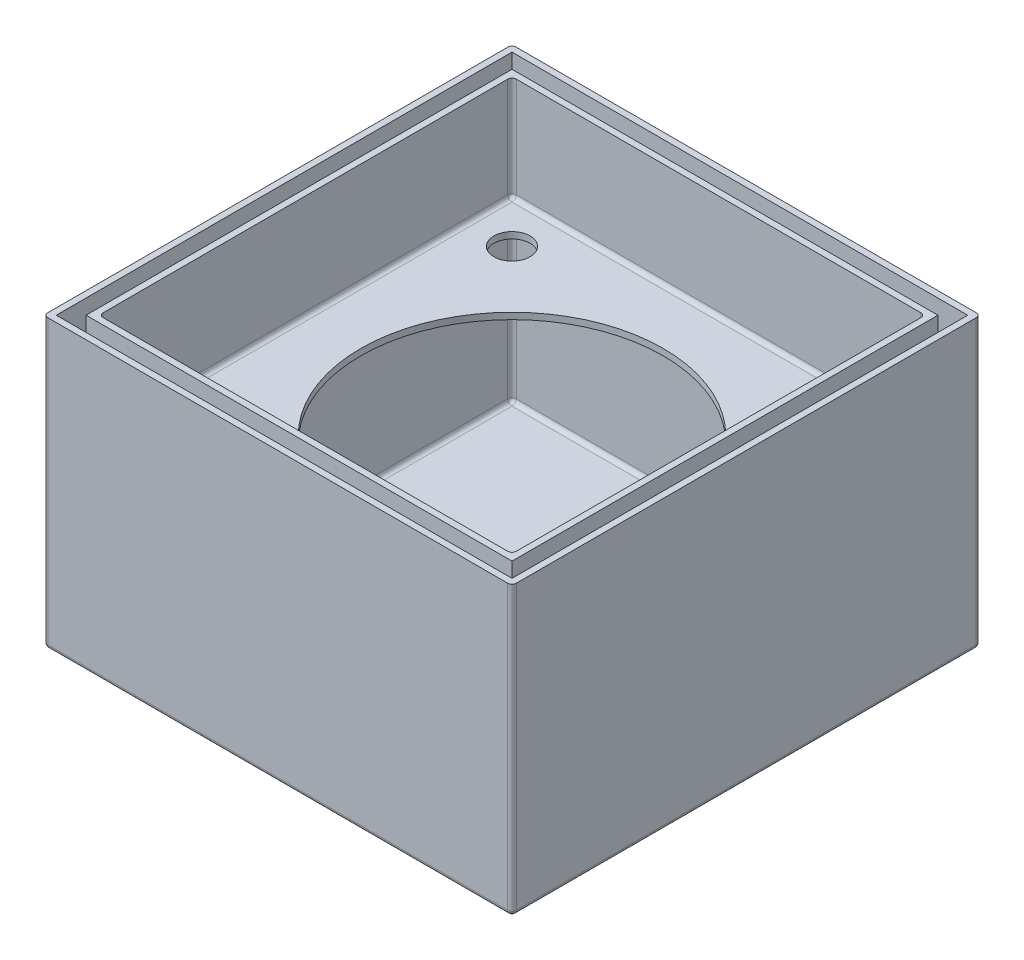
SolidWorks part; units mm, degrees
material "Nylon 101"
ref_plane "Front Plane" through (0, 0, 0) normal (0, 0, 1) x (1, 0, 0)
ref_plane "Top Plane" through (0, 0, 0) normal (0, 1, 0) x (1, 0, 0)
ref_plane "Right Plane" through (0, 0, 0) normal (1, 0, 0) x (0, 0, -1)
sketch "Sketch1" plane through (0, 0, 0) normal (0, 1, 0) x (1, 0, 0)
  line L0 (-100, 100) -> (100, 100)
  line L1 (-97, 97) -> (97, 97)
  line L2 (-97, 97) -> (-97, -97)
  line L3 (-97, -97) -> (97, -97)
  line L4 (97, 97) -> (97, -97)
  line L5 (-97, 97) -> (97, -97) construction
  line L6 (-97, -97) -> (97, 97) construction
  line L7 (100, 100) -> (100, -100)
  line L8 (-100, -100) -> (100, -100)
  line L9 (-100, 100) -> (-100, -100)
  line L10 (-107, -107) -> (107, -107)
  line L11 (107, 107) -> (107, -107)
  line L12 (-107, 107) -> (107, 107)
  line L13 (-107, 107) -> (-107, -107)
  line L14 (-110, -110) -> (110, -110)
  line L15 (110, 110) -> (110, -110)
  line L16 (-110, 110) -> (110, 110)
  line L17 (-110, 110) -> (-110, -110)
  point P0 (0, 0)
  dimension "D1" = 194
  dimension "D2" = 194
  dimension "D3" = 3
  dimension "D4" = 7
  dimension "D5" = 3
extrude "Boss-Extrude1" add sketch "Sketch1" along normal blind 132 contours L0 L9 L8 L7 L1 L4 L3 L2 | L16 L17 L14 L15 L13 L12 L11 L10
sketch "Sketch3" plane through (0, 0, 0) normal (0, -1, 0) x (1, 0, 0)
  line L1 (-110, -110) -> (110, -110)
  line L2 (-110, -110) -> (-110, 110)
  line L3 (-110, 110) -> (110, 110)
  line L4 (110, -110) -> (110, 110)
  line L5 (-110, -110) -> (110, 110) construction
  line L6 (-110, 110) -> (110, -110) construction
  point P0 (0, 0)
extrude "Boss-Extrude3" add sketch "Sketch3" along normal blind 3
ref_plane "Plane1" through (0, 80, 0) normal (0, 1, 0) x (1, 0, 0)
sketch "Sketch4" plane through (0, 80, 0) normal (0, 1, 0) x (1, 0, 0)
  line L1 (-97, -97) -> (97, -97)
  line L2 (-97, -97) -> (-97, 97)
  line L3 (-97, 97) -> (97, 97)
  line L4 (97, -97) -> (97, 97)
  line L5 (-97, -97) -> (97, 97) construction
  line L6 (-97, 97) -> (97, -97) construction
  point P0 (0, 0)
extrude "Boss-Extrude4" add sketch "Sketch4" along normal blind 3
sketch "Sketch5" plane through (0, 83, 0) normal (0, 1, 0) x (1, 0, 0)
  circle A0 centre (0, 0) radius 71
  dimension "D1" = 142
extrude "Cut-Extrude1" cut sketch "Sketch5" against normal blind 3
sketch "Sketch6" plane through (0, 83, 0) normal (0, 1, 0) x (1, 0, 0)
  line L0 (-97, 97) -> (97, 97) construction
  line L1 (97, -97) -> (97, 97) construction
  circle A0 centre (70, 70) radius 21.5154
  dimension "D1" = 27
  dimension "D2" = 27
extrude "Cut-Extrude2" [suppressed] cut sketch "Sketch6" against normal blind 3
sketch "Sketch7" plane through (0, 83, 0) normal (0, 1, 0) x (1, 0, 0)
  line L0 (97, 97) -> (-97, 97) construction
  line L1 (-97, 97) -> (-97, -97) construction
  circle A0 centre (-77, 77) radius 8.5
  dimension "D1" = 17
  dimension "D2" = 20
  dimension "D3" = 20
extrude "Cut-Extrude3" cut sketch "Sketch7" against normal blind 3
fillet "Fillet1" radius 2 24 edges at (97, 107.5, -97) (-97, 107.5, -97) (-97, 107.5, 97) (97, 107.5, 97) (0, 83, -97) (-97, 83, 0) (0, 83, 97) (97, 83, 0) (110, 64.5, 110) (110, 64.5, -110) (-110, 64.5, -110) (-110, 64.5, 110) (-97, 0, 0) (0, 0, 97) (0, 0, -97) (97, 0, 0) (97, 40, -97) (97, 40, 97) (-97, 40, 97) (-97, 40, -97) (0, -3, 110) (-110, -3, 0) (110, -3, 0) (0, -3, -110)
